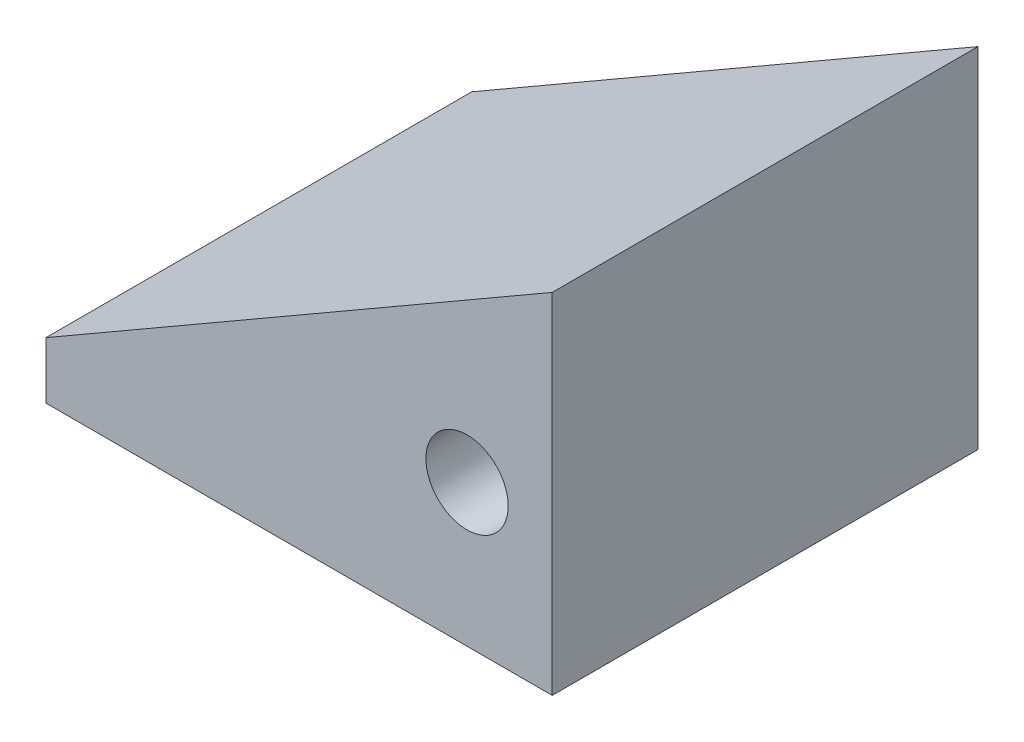
SolidWorks part; units mm, degrees
material "PA Tipo 6"
ref_plane "Plano frontal" through (0, 0, 0) normal (0, 0, 1) x (1, 0, 0)
ref_plane "Plano superior" through (0, 0, 0) normal (0, 1, 0) x (1, 0, 0)
ref_plane "Plano direito" through (0, 0, 0) normal (1, 0, 0) x (0, 0, -1)
sketch "Esboço1" plane through (0, 0, 0) normal (0, 0, 1) x (1, 0, 0)
  line L0 (0, 0) -> (17.8326, 10.2956)
  line L4 (17.8326, 0.2956) -> (17.8326, 10.2956)
  line L5 (0, 0) -> (0, -2)
  line L6 (0, -2) -> (17.8326, -2)
  line L7 (17.8326, -2) -> (17.8326, 0.2956)
  dimension "D1" = 30
  dimension "D2" = 10
  dimension "D3" = 2
extrude "Ressalto-extrusão1" add sketch "Esboço1" along normal blind 15
sketch "Esboço2" plane through (0, 0, 15) normal (0, 0, 1) x (1, 0, 0)
  line L0 (17.8326, -2) -> (17.8326, 10.2956) construction
  line L2 (0, -2) -> (17.8326, -2) construction
  circle A0 centre (14.8326, 3) radius 1.45
  dimension "D1" = 2.9
  dimension "D2" = 3
  dimension "D3" = 5
extrude "Corte-extrusão1" cut sketch "Esboço2" against normal through all both and the other way through all
